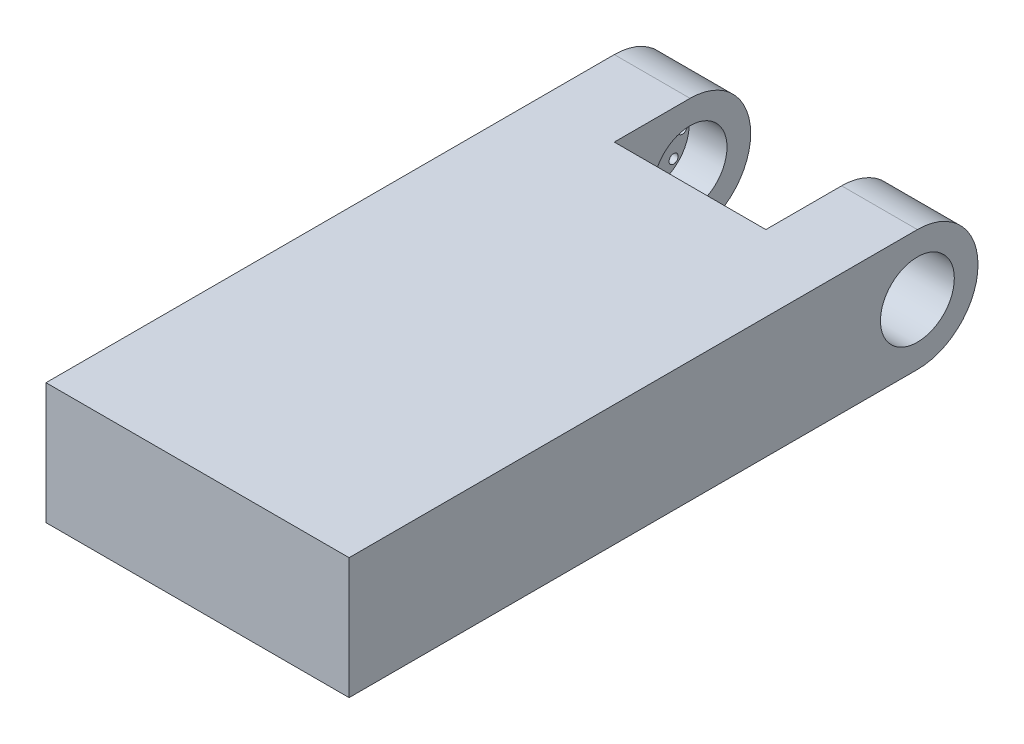
SolidWorks part; units mm, degrees
ref_plane "정면" through (0, 0, 0) normal (0, 0, 1) x (1, 0, 0)
ref_plane "윗면" through (0, 0, 0) normal (0, 1, 0) x (1, 0, 0)
ref_plane "우측면" through (0, 0, 0) normal (1, 0, 0) x (0, 0, -1)
sketch "Sketch1" plane through (0, 0, 0) normal (1, 0, 0) x (0, 0, -1)
  line L1 (0, 0) -> (150, 0)
  line L2 (0, 0) -> (0, 32)
  line L3 (0, 32) -> (150, 32)
  arc A1 (150, 32) -> (150, 0) centre (150, 16) cw
  dimension "D1" = 32
  dimension "D2" = 150
extrude "Boss-Extrude1" add sketch "Sketch1" along normal blind 80 contours L3 A1 L1 L2
sketch "Sketch2" plane through (0, 32, 0) normal (0, 1, 0) x (1, 0, 0)
  line L0 (40, 150) -> (40, 194.7163) construction
  line L1 (80, 150) -> (0, 150) construction
  line L3 (20, 130) -> (60, 130)
  line L4 (20, 130) -> (20, 170)
  line L5 (20, 170) -> (60, 170)
  line L6 (60, 130) -> (60, 170)
  line L7 (20, 130) -> (60, 170) construction
  line L8 (20, 170) -> (60, 130) construction
extrude "Cut-Extrude1" cut sketch "Sketch2" against normal blind 60
sketch "Sketch3" plane through (80, 0, 0) normal (1, 0, 0) x (0, 0, -1)
  circle A0 centre (150, 16) radius 9.75
  dimension "D1" = 19.5
extrude "Cut-Extrude2" cut sketch "Sketch3" against normal blind 70
sketch "Sketch4" plane through (0, 0, 0) normal (-1, 0, 0) x (0, 0, 1)
  circle A0 centre (-150, 16) radius 8 construction
  point P3 (-150, 24)
  point P6 (-144.3431, 21.6569)
  point P7 (-142, 16)
  point P8 (-144.3431, 10.3431)
  point P9 (-150, 8)
  point P10 (-155.6569, 10.3431)
  point P11 (-158, 16)
  point P12 (-155.6569, 21.6569)
  point P13 (-150, 16)
  dimension "D1" = 16
  dimension "D2" = 8
hole_wizard "CBORE for M2 Cheese Slotted Head3" positions "3DSketch1" profile "Sketch5" counterbore size "M2" standard "KS" end condition up to next
sketch3d "3DSketch1"
  point P0 (0, 24, -150)
  point P3 (0, 21.6569, -144.3431)
  point P6 (0, 16, -142)
  point P9 (0, 10.3431, -144.3431)
  point P12 (0, 8, -150)
  point P15 (0, 10.3431, -155.6569)
  point P18 (0, 16, -158)
  point P21 (0, 21.6569, -155.6569)
sketch "Sketch5" plane through (0, 24, -150) normal (0, 1, 0) x (0, 0, 1)
  line L0 (0, 0) -> (0, 10)
  line L1 (0, 10) -> (1.2, 10)
  line L3 (1.2, 10) -> (1.2, 1.4)
  line L4 (1.2, 1.4) -> (2.4, 1.4)
  line L5 (2.4, 1.4) -> (2.4, 0)
  line L7 (2.4, 0) -> (0, 0)
  line L11 (0, -6.35) -> (0, 107.95) construction
  dimension "Thru Hole Dia." = 2.4
  dimension "Thru Hole Depth" = 10
  dimension "C'Bore Dia." = 4.8
  dimension "C'Bore Depth" = 1.4
